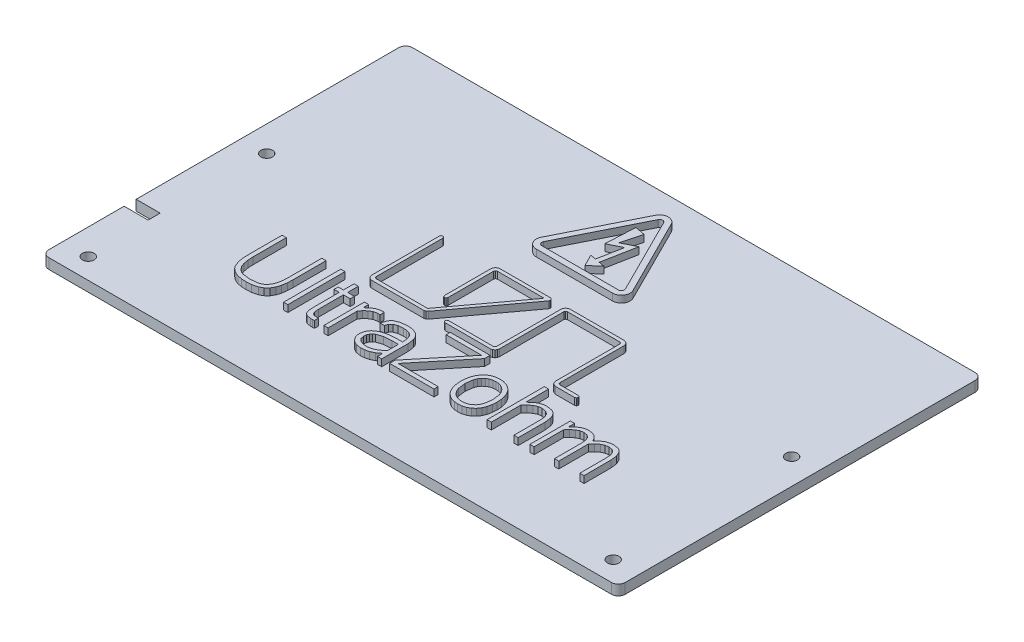
SolidWorks part; units mm, degrees
ref_plane "Ebene vorne" through (0, 0, 0) normal (0, 0, 1) x (1, 0, 0)
ref_plane "Ebene oben" through (0, 0, 0) normal (0, 1, 0) x (1, 0, 0)
ref_plane "Ebene rechts" through (0, 0, 0) normal (1, 0, 0) x (0, 0, -1)
sketch "Skizze1" plane through (0, 0, 0) normal (0, 1, 0) x (1, 0, 0)
  line L1 (-82, -53) -> (82, -53)
  line L2 (-84, -51) -> (-84, 51)
  line L3 (-82, 53) -> (82, 53)
  line L4 (84, -51) -> (84, 51)
  line L5 (-84, -53) -> (84, 53) construction
  line L6 (-84, 53) -> (84, -53) construction
  arc A0 (82, -53) -> (84, -51) centre (82, -51) ccw
  arc A1 (82, 53) -> (84, 51) centre (82, 51) cw
  arc A2 (-84, 51) -> (-82, 53) centre (-82, 51) cw
  arc A3 (-82, -53) -> (-84, -51) centre (-82, -51) cw
  point P0 (0, 0)
  dimension "D3" = 2
  dimension "D1" = 168
  dimension "D2" = 106
extrude "Aufsatz-Linear austragen1" add sketch "Skizze1" along normal blind 3
sketch "Skizze4" plane through (0, 3, 0) normal (0, 1, 0) x (1, 0, 0)
  line L0 (-84, 51) -> (-84, -51) construction
  line L1 (-84, -29.05) -> (-77, -29.05)
  line L2 (-84, -29.05) -> (-84, -25.55)
  line L3 (-84, -25.55) -> (-77, -25.55)
  line L4 (-77, -29.05) -> (-77, -25.55)
  line L5 (-77, -27.3) -> (-84, -27.3) construction
  line L6 (-82, -53) -> (82, -53) construction
  dimension "D1" = 25.7
  dimension "D2" = 3.5
  dimension "D3" = 7
extrude "Schnitt-Linear austragen3" cut sketch "Skizze4" against normal blind 3
sketch "Skizze9" plane through (0, 3, 0) normal (0, 1, 0) x (1, 0, 0)
  line L0 (-12.0391, -13.6755) -> (-27.171, -13.6755)
  line L1 (-27.171, -13.6755) -> (-27.7014, -13.5675)
  line L2 (-27.7014, -13.5675) -> (-28.1343, -13.2749)
  line L3 (-28.1343, -13.2749) -> (-28.4261, -12.8414)
  line L4 (-28.4261, -12.8414) -> (-28.5331, -12.3109)
  line L5 (-28.5331, -12.3109) -> (-28.5331, 7.3376)
  line L6 (-28.5331, 7.3376) -> (-28.3811, 7.7047)
  line L7 (-28.3811, 7.7047) -> (-28.014, 7.8567)
  line L8 (-28.014, 7.8567) -> (-27.6485, 7.7038)
  line L9 (-27.6485, 7.7038) -> (-27.4973, 7.3376)
  line L10 (-27.4973, 7.3376) -> (-27.4973, -12.1082)
  line L11 (-27.4973, -12.1082) -> (-27.3451, -12.4744)
  line L12 (-27.3451, -12.4744) -> (-26.9782, -12.6248)
  line L13 (-26.9782, -12.6248) -> (-12.0391, -12.6248)
  line L14 (-12.0391, -12.6248) -> (-11.9303, -12.568)
  line L15 (-11.9303, -12.568) -> (2.2992, 6.7146)
  line L16 (2.2992, 6.7146) -> (2.3115, 6.8581)
  line L17 (2.3115, 6.8581) -> (2.188, 6.9322)
  line L18 (2.188, 6.9322) -> (-11.2282, 6.9322)
  line L19 (-11.2282, 6.9322) -> (-11.5953, 6.7801)
  line L20 (-11.5953, 6.7801) -> (-11.7474, 6.413)
  line L21 (-11.7474, 6.413) -> (-11.7474, -6.9068)
  line L22 (-11.7474, -6.9068) -> (-11.8978, -7.2737)
  line L23 (-11.8978, -7.2737) -> (-12.2641, -7.4259)
  line L24 (-12.2641, -7.4259) -> (-12.6312, -7.2739)
  line L25 (-12.6312, -7.2739) -> (-12.7832, -6.9068)
  line L26 (-12.7832, -6.9068) -> (-12.7832, 6.596)
  line L27 (-12.7832, 6.596) -> (-12.6762, 7.1262)
  line L28 (-12.6762, 7.1262) -> (-12.3842, 7.5591)
  line L29 (-12.3842, 7.5591) -> (-11.9513, 7.8511)
  line L30 (-11.9513, 7.8511) -> (-11.4211, 7.9581)
  line L31 (-11.4211, 7.9581) -> (3.1645, 7.9581)
  line L32 (3.1645, 7.9581) -> (3.5356, 7.8718)
  line L33 (3.5356, 7.8718) -> (3.7978, 7.5953)
  line L34 (3.7978, 7.5953) -> (3.8644, 7.2202)
  line L35 (3.8644, 7.2202) -> (3.7133, 6.8704)
  line L36 (3.7133, 6.8704) -> (-11.1022, -13.181)
  line L37 (-11.1022, -13.181) -> (-11.515, -13.5337)
  line L38 (-11.515, -13.5337) -> (-12.0391, -13.6755)
  line L39 (-12.0391, -13.6755) -> (-12.0391, -13.6755)
  line L40 (31.9376, -13.6755) -> (26.3901, -13.6755)
  line L41 (26.3901, -13.6755) -> (25.8597, -13.5675)
  line L42 (25.8597, -13.5675) -> (25.4268, -13.2749)
  line L43 (25.4268, -13.2749) -> (25.135, -12.8414)
  line L44 (25.135, -12.8414) -> (25.028, -12.3109)
  line L45 (25.028, -12.3109) -> (25.028, 6.4056)
  line L46 (25.028, 6.4056) -> (24.8768, 6.7718)
  line L47 (24.8768, 6.7718) -> (24.5113, 6.9248)
  line L48 (24.5113, 6.9248) -> (9.2187, 6.9248)
  line L49 (9.2187, 6.9248) -> (8.8532, 6.7718)
  line L50 (8.8532, 6.7718) -> (8.702, 6.4056)
  line L51 (8.702, 6.4056) -> (8.702, -12.2985)
  line L52 (8.702, -12.2985) -> (8.6022, -12.8234)
  line L53 (8.6022, -12.8234) -> (8.3085, -13.2697)
  line L54 (8.3085, -13.2697) -> (7.8659, -13.569)
  line L55 (7.8659, -13.569) -> (7.3424, -13.6755)
  line L56 (7.3424, -13.6755) -> (-5.8514, -13.6755)
  line L57 (-5.8514, -13.6755) -> (-6.2185, -13.5234)
  line L58 (-6.2185, -13.5234) -> (-6.3705, -13.1563)
  line L59 (-6.3705, -13.1563) -> (-6.2185, -12.7892)
  line L60 (-6.2185, -12.7892) -> (-5.8514, -12.6372)
  line L61 (-5.8514, -12.6372) -> (7.1471, -12.6372)
  line L62 (7.1471, -12.6372) -> (7.514, -12.4867)
  line L63 (7.514, -12.4867) -> (7.6662, -12.1205)
  line L64 (7.6662, -12.1205) -> (7.6662, 6.596)
  line L65 (7.6662, 6.596) -> (7.7699, 7.1172)
  line L66 (7.7699, 7.1172) -> (8.0652, 7.5591)
  line L67 (8.0652, 7.5591) -> (8.5071, 7.8544)
  line L68 (8.5071, 7.8544) -> (9.0284, 7.9581)
  line L69 (9.0284, 7.9581) -> (24.7016, 7.9581)
  line L70 (24.7016, 7.9581) -> (25.2229, 7.8544)
  line L71 (25.2229, 7.8544) -> (25.6648, 7.5591)
  line L72 (25.6648, 7.5591) -> (25.9601, 7.1172)
  line L73 (25.9601, 7.1172) -> (26.0638, 6.596)
  line L74 (26.0638, 6.596) -> (26.0638, -12.1106)
  line L75 (26.0638, -12.1106) -> (26.216, -12.4768)
  line L76 (26.216, -12.4768) -> (26.5829, -12.6273)
  line L77 (26.5829, -12.6273) -> (31.9376, -12.6273)
  line L78 (31.9376, -12.6273) -> (32.3031, -12.7802)
  line L79 (32.3031, -12.7802) -> (32.4542, -13.1464)
  line L80 (32.4542, -13.1464) -> (32.3066, -13.5191)
  line L81 (32.3066, -13.5191) -> (31.9376, -13.6755)
  line L82 (-45.2447, -32.34) -> (-46.5411, -32.2746)
  line L83 (-46.5411, -32.2746) -> (-47.8157, -32.0285)
  line L84 (-47.8157, -32.0285) -> (-48.7416, -31.6863)
  line L85 (-48.7416, -31.6863) -> (-49.5907, -31.1831)
  line L86 (-49.5907, -31.1831) -> (-50.2138, -30.6155)
  line L87 (-50.2138, -30.6155) -> (-50.7106, -29.9347)
  line L88 (-50.7106, -29.9347) -> (-51.341, -28.4118)
  line L89 (-51.341, -28.4118) -> (-51.6104, -26.7357)
  line L90 (-51.6104, -26.7357) -> (-51.6648, -25.0448)
  line L91 (-51.6648, -25.0448) -> (-51.6648, -15.3565)
  line L92 (-51.6648, -15.3565) -> (-50.4287, -15.3565)
  line L93 (-50.4287, -15.3565) -> (-50.4287, -24.9978)
  line L94 (-50.4287, -24.9978) -> (-50.3617, -26.5597)
  line L95 (-50.3617, -26.5597) -> (-50.0826, -28.0979)
  line L96 (-50.0826, -28.0979) -> (-49.694, -29.0952)
  line L97 (-49.694, -29.0952) -> (-49.0691, -29.9643)
  line L98 (-49.0691, -29.9643) -> (-48.3174, -30.5337)
  line L99 (-48.3174, -30.5337) -> (-47.4399, -30.879)
  line L100 (-47.4399, -30.879) -> (-45.2373, -31.1262)
  line L101 (-45.2373, -31.1262) -> (-43.0124, -30.879)
  line L102 (-43.0124, -30.879) -> (-42.1317, -30.5347)
  line L103 (-42.1317, -30.5347) -> (-41.3832, -29.9569)
  line L104 (-41.3832, -29.9569) -> (-40.7738, -29.0846)
  line L105 (-40.7738, -29.0846) -> (-40.3944, -28.0904)
  line L106 (-40.3944, -28.0904) -> (-40.1223, -26.5554)
  line L107 (-40.1223, -26.5554) -> (-40.0582, -24.9978)
  line L108 (-40.0582, -24.9978) -> (-40.0582, -15.3565)
  line L109 (-40.0582, -15.3565) -> (-38.8221, -15.3565)
  line L110 (-38.8221, -15.3565) -> (-38.8221, -25.0473)
  line L111 (-38.8221, -25.0473) -> (-38.8865, -26.5926)
  line L112 (-38.8865, -26.5926) -> (-39.1138, -28.1226)
  line L113 (-39.1138, -28.1226) -> (-39.4909, -29.3269)
  line L114 (-39.4909, -29.3269) -> (-40.1274, -30.4167)
  line L115 (-40.1274, -30.4167) -> (-41.0155, -31.2668)
  line L116 (-41.0155, -31.2668) -> (-42.1002, -31.8456)
  line L117 (-42.1002, -31.8456) -> (-43.6494, -32.2393)
  line L118 (-43.6494, -32.2393) -> (-45.2447, -32.34)
  line L119 (-33.2944, -32.036) -> (-34.5305, -32.036)
  line L120 (-34.5305, -32.036) -> (-34.5305, -15.3565)
  line L121 (-34.5305, -15.3565) -> (-33.2944, -15.3565)
  line L122 (-33.2944, -15.3565) -> (-33.2944, -32.036)
  line L123 (-25.4306, -32.1423) -> (-25.9522, -32.1892)
  line L124 (-25.9522, -32.1892) -> (-26.4738, -32.2041)
  line L125 (-26.4738, -32.2041) -> (-27.7569, -31.9816)
  line L126 (-27.7569, -31.9816) -> (-28.1822, -31.7113)
  line L127 (-28.1822, -31.7113) -> (-28.4985, -31.319)
  line L128 (-28.4985, -31.319) -> (-28.8298, -30.2165)
  line L129 (-28.8298, -30.2165) -> (-28.9064, -28.6689)
  line L130 (-28.9064, -28.6689) -> (-28.9064, -21.4503)
  line L131 (-28.9064, -21.4503) -> (-30.4268, -21.4503)
  line L132 (-30.4268, -21.4503) -> (-30.4268, -20.2316)
  line L133 (-30.4268, -20.2316) -> (-28.9064, -20.2316)
  line L134 (-28.9064, -20.2316) -> (-28.9064, -17.1365)
  line L135 (-28.9064, -17.1365) -> (-27.6704, -17.1365)
  line L136 (-27.6704, -17.1365) -> (-27.6704, -20.2291)
  line L137 (-27.6704, -20.2291) -> (-25.7198, -20.2291)
  line L138 (-25.7198, -20.2291) -> (-25.7198, -21.4478)
  line L139 (-25.7198, -21.4478) -> (-27.6704, -21.4478)
  line L140 (-27.6704, -21.4478) -> (-27.6704, -28.7728)
  line L141 (-27.6704, -28.7728) -> (-27.5616, -29.9396)
  line L142 (-27.5616, -29.9396) -> (-27.2402, -30.6095)
  line L143 (-27.2402, -30.6095) -> (-26.7112, -30.9136)
  line L144 (-26.7112, -30.9136) -> (-25.9967, -30.9828)
  line L145 (-25.9967, -30.9828) -> (-25.705, -30.9828)
  line L146 (-25.705, -30.9828) -> (-25.4281, -30.968)
  line L147 (-25.4281, -30.968) -> (-25.4306, -32.1423)
  line L148 (-17.3047, -21.1759) -> (-17.6731, -21.1462)
  line L149 (-17.6731, -21.1462) -> (-18.1205, -21.1462)
  line L150 (-18.1205, -21.1462) -> (-19.1366, -21.3588)
  line L151 (-19.1366, -21.3588) -> (-20.0735, -21.9151)
  line L152 (-20.0735, -21.9151) -> (-20.9017, -22.6913)
  line L153 (-20.9017, -22.6913) -> (-21.5617, -23.5813)
  line L154 (-21.5617, -23.5813) -> (-21.5617, -32.036)
  line L155 (-21.5617, -32.036) -> (-22.7978, -32.036)
  line L156 (-22.7978, -32.036) -> (-22.7978, -20.2316)
  line L157 (-22.7978, -20.2316) -> (-21.5617, -20.2316)
  line L158 (-21.5617, -20.2316) -> (-21.5617, -21.8607)
  line L159 (-21.5617, -21.8607) -> (-20.5259, -20.8718)
  line L160 (-20.5259, -20.8718) -> (-19.5371, -20.2761)
  line L161 (-19.5371, -20.2761) -> (-18.6075, -19.9942)
  line L162 (-18.6075, -19.9942) -> (-17.7942, -19.9275)
  line L163 (-17.7942, -19.9275) -> (-17.5643, -19.9275)
  line L164 (-17.5643, -19.9275) -> (-17.3171, -19.9497)
  line L165 (-17.3171, -19.9497) -> (-17.3047, -21.1759)
  line L166 (-7.169, -30.5131) -> (-8.4051, -31.4179)
  line L167 (-8.4051, -31.4179) -> (-9.5793, -31.9816)
  line L168 (-9.5793, -31.9816) -> (-10.7239, -32.2634)
  line L169 (-10.7239, -32.2634) -> (-11.8759, -32.34)
  line L170 (-11.8759, -32.34) -> (-13.3345, -32.1052)
  line L171 (-13.3345, -32.1052) -> (-14.5013, -31.4352)
  line L172 (-14.5013, -31.4352) -> (-15.2776, -30.3821)
  line L173 (-15.2776, -30.3821) -> (-15.4947, -29.7167)
  line L174 (-15.4947, -29.7167) -> (-15.5619, -29.02)
  line L175 (-15.5619, -29.02) -> (-15.4598, -28.0761)
  line L176 (-15.4598, -28.0761) -> (-15.1192, -27.2069)
  line L177 (-15.1192, -27.2069) -> (-14.5642, -26.4563)
  line L178 (-14.5642, -26.4563) -> (-13.819, -25.868)
  line L179 (-13.819, -25.868) -> (-12.8385, -25.3748)
  line L180 (-12.8385, -25.3748) -> (-11.6398, -25.0225)
  line L181 (-11.6398, -25.0225) -> (-10.223, -24.8112)
  line L182 (-10.223, -24.8112) -> (-8.588, -24.7407)
  line L183 (-8.588, -24.7407) -> (-7.1764, -24.7407)
  line L184 (-7.1764, -24.7407) -> (-7.2679, -23.3094)
  line L185 (-7.2679, -23.3094) -> (-7.698, -22.1746)
  line L186 (-7.698, -22.1746) -> (-8.138, -21.7262)
  line L187 (-8.138, -21.7262) -> (-8.6869, -21.4207)
  line L188 (-8.6869, -21.4207) -> (-9.5724, -21.1974)
  line L189 (-9.5724, -21.1974) -> (-10.4841, -21.1462)
  line L190 (-10.4841, -21.1462) -> (-11.947, -21.2754)
  line L191 (-11.947, -21.2754) -> (-12.9933, -21.6629)
  line L192 (-12.9933, -21.6629) -> (-13.6706, -22.3326)
  line L193 (-13.6706, -22.3326) -> (-13.9822, -23.2327)
  line L194 (-13.9822, -23.2327) -> (-15.196, -23.2327)
  line L195 (-15.196, -23.2327) -> (-14.7733, -21.7717)
  line L196 (-14.7733, -21.7717) -> (-14.3839, -21.2025)
  line L197 (-14.3839, -21.2025) -> (-13.8759, -20.7408)
  line L198 (-13.8759, -20.7408) -> (-12.4637, -20.1296)
  line L199 (-12.4637, -20.1296) -> (-10.4965, -19.9275)
  line L200 (-10.4965, -19.9275) -> (-9.4282, -19.9913)
  line L201 (-9.4282, -19.9913) -> (-8.3853, -20.2316)
  line L202 (-8.3853, -20.2316) -> (-7.626, -20.5846)
  line L203 (-7.626, -20.5846) -> (-6.9712, -21.1067)
  line L204 (-6.9712, -21.1067) -> (-6.4927, -21.7528)
  line L205 (-6.4927, -21.7528) -> (-6.1802, -22.4936)
  line L206 (-6.1802, -22.4936) -> (-5.9329, -24.3279)
  line L207 (-5.9329, -24.3279) -> (-5.9329, -32.036)
  line L208 (-5.9329, -32.036) -> (-7.169, -32.036)
  line L209 (-7.169, -32.036) -> (-7.169, -30.5131)
  line L210 (-7.169, -25.9595) -> (-9.0256, -25.9595)
  line L211 (-9.0256, -25.9595) -> (-11.3599, -26.1498)
  line L212 (-11.3599, -26.1498) -> (-13.0131, -26.7209)
  line L213 (-13.0131, -26.7209) -> (-13.566, -27.1069)
  line L214 (-13.566, -27.1069) -> (-13.9827, -27.6211)
  line L215 (-13.9827, -27.6211) -> (-14.2427, -28.2296)
  line L216 (-14.2427, -28.2296) -> (-14.3258, -28.8988)
  line L217 (-14.3258, -28.8988) -> (-14.1223, -29.8246)
  line L218 (-14.1223, -29.8246) -> (-13.4952, -30.5354)
  line L219 (-13.4952, -30.5354) -> (-12.5131, -30.9748)
  line L220 (-12.5131, -30.9748) -> (-11.2233, -31.1213)
  line L221 (-11.2233, -31.1213) -> (-10.0021, -30.9309)
  line L222 (-10.0021, -30.9309) -> (-8.8871, -30.4365)
  line L223 (-8.8871, -30.4365) -> (-7.9279, -29.7591)
  line L224 (-7.9279, -29.7591) -> (-7.169, -29.0348)
  line L225 (-7.169, -29.0348) -> (-7.169, -25.9595)
  line L226 (9.2954, -32.036) -> (-3.6388, -32.036)
  line L227 (-3.6388, -32.036) -> (-3.6388, -30.4217)
  line L228 (-3.6388, -30.4217) -> (7.7132, -16.5778)
  line L229 (7.7132, -16.5778) -> (-2.6401, -16.5778)
  line L230 (-2.6401, -16.5778) -> (-2.6401, -15.3565)
  line L231 (-2.6401, -15.3565) -> (8.9789, -15.3565)
  line L232 (8.9789, -15.3565) -> (8.9789, -16.9881)
  line L233 (8.9789, -16.9881) -> (-2.3929, -30.8172)
  line L234 (-2.3929, -30.8172) -> (9.2954, -30.8172)
  line L235 (9.2954, -30.8172) -> (9.2954, -32.036)
  line L236 (16.4892, -19.9275) -> (17.6108, -20.027)
  line L237 (17.6108, -20.027) -> (18.6894, -20.3502)
  line L238 (18.6894, -20.3502) -> (19.5967, -20.8628)
  line L239 (19.5967, -20.8628) -> (20.3631, -21.569)
  line L240 (20.3631, -21.569) -> (20.9971, -22.4874)
  line L241 (20.9971, -22.4874) -> (21.4335, -23.5145)
  line L242 (21.4335, -23.5145) -> (21.7144, -24.8122)
  line L243 (21.7144, -24.8122) -> (21.808, -26.1301)
  line L244 (21.808, -26.1301) -> (21.7144, -27.4479)
  line L245 (21.7144, -27.4479) -> (21.4335, -28.7456)
  line L246 (21.4335, -28.7456) -> (20.999, -29.778)
  line L247 (20.999, -29.778) -> (20.368, -30.7035)
  line L248 (20.368, -30.7035) -> (19.5999, -31.4091)
  line L249 (19.5999, -31.4091) -> (18.6919, -31.9222)
  line L250 (18.6919, -31.9222) -> (17.6183, -32.2325)
  line L251 (17.6183, -32.2325) -> (16.5152, -32.336)
  line L252 (16.5152, -32.336) -> (15.4121, -32.2325)
  line L253 (15.4121, -32.2325) -> (14.3385, -31.9222)
  line L254 (14.3385, -31.9222) -> (13.4343, -31.4143)
  line L255 (13.4343, -31.4143) -> (12.6723, -30.7109)
  line L256 (12.6723, -30.7109) -> (12.0371, -29.7855)
  line L257 (12.0371, -29.7855) -> (11.5969, -28.753)
  line L258 (11.5969, -28.753) -> (11.3123, -27.4481)
  line L259 (11.3123, -27.4481) -> (11.2174, -26.1226)
  line L260 (11.2174, -26.1226) -> (11.3123, -24.7972)
  line L261 (11.3123, -24.7972) -> (11.5969, -23.4923)
  line L262 (11.5969, -23.4923) -> (12.032, -22.4664)
  line L263 (12.032, -22.4664) -> (12.6649, -21.5492)
  line L264 (12.6649, -21.5492) -> (13.432, -20.8473)
  line L265 (13.432, -20.8473) -> (14.3385, -20.3379)
  line L266 (14.3385, -20.3379) -> (15.3933, -20.0246)
  line L267 (15.3933, -20.0246) -> (16.4892, -19.9275)
  line L268 (16.4892, -31.1213) -> (17.3305, -31.0481)
  line L269 (17.3305, -31.0481) -> (18.1406, -30.8098)
  line L270 (18.1406, -30.8098) -> (18.8389, -30.4147)
  line L271 (18.8389, -30.4147) -> (19.4237, -29.8654)
  line L272 (19.4237, -29.8654) -> (19.9207, -29.1227)
  line L273 (19.9207, -29.1227) -> (20.2592, -28.2956)
  line L274 (20.2592, -28.2956) -> (20.5608, -26.1177)
  line L275 (20.5608, -26.1177) -> (20.2592, -23.9397)
  line L276 (20.2592, -23.9397) -> (19.9216, -23.1204)
  line L277 (19.9216, -23.1204) -> (19.4237, -22.3873)
  line L278 (19.4237, -22.3873) -> (18.8366, -21.8474)
  line L279 (18.8366, -21.8474) -> (18.1406, -21.4577)
  line L280 (18.1406, -21.4577) -> (17.3222, -21.2242)
  line L281 (17.3222, -21.2242) -> (16.4818, -21.1463)
  line L282 (16.4818, -21.1463) -> (15.6415, -21.2242)
  line L283 (15.6415, -21.2242) -> (14.823, -21.4577)
  line L284 (14.823, -21.4577) -> (14.1271, -21.8474)
  line L285 (14.1271, -21.8474) -> (13.54, -22.3873)
  line L286 (13.54, -22.3873) -> (13.0443, -23.12)
  line L287 (13.0443, -23.12) -> (12.7118, -23.9397)
  line L288 (12.7118, -23.9397) -> (12.4201, -26.1177)
  line L289 (12.4201, -26.1177) -> (12.7118, -28.2956)
  line L290 (12.7118, -28.2956) -> (13.0454, -29.123)
  line L291 (13.0454, -29.123) -> (13.54, -29.8654)
  line L292 (13.54, -29.8654) -> (14.1248, -30.4147)
  line L293 (14.1248, -30.4147) -> (14.823, -30.8098)
  line L294 (14.823, -30.8098) -> (15.6406, -31.0488)
  line L295 (15.6406, -31.0488) -> (16.4892, -31.1213)
  line L296 (26.0143, -21.9843) -> (27.1565, -20.9163)
  line L297 (27.1565, -20.9163) -> (28.2491, -20.2934)
  line L298 (28.2491, -20.2934) -> (29.2627, -20.0041)
  line L299 (29.2627, -20.0041) -> (30.1749, -19.9275)
  line L300 (30.1749, -19.9275) -> (31.781, -20.1959)
  line L301 (31.781, -20.1959) -> (32.412, -20.5313)
  line L302 (32.412, -20.5313) -> (32.9283, -21.001)
  line L303 (32.9283, -21.001) -> (33.3298, -21.6049)
  line L304 (33.3298, -21.6049) -> (33.6166, -22.3429)
  line L305 (33.6166, -22.3429) -> (33.846, -24.2216)
  line L306 (33.846, -24.2216) -> (33.846, -32.036)
  line L307 (33.846, -32.036) -> (32.61, -32.036)
  line L308 (32.61, -32.036) -> (32.61, -24.3279)
  line L309 (32.61, -24.3279) -> (32.4641, -22.9039)
  line L310 (32.4641, -22.9039) -> (31.9895, -21.9151)
  line L311 (31.9895, -21.9151) -> (31.1292, -21.3366)
  line L312 (31.1292, -21.3366) -> (29.8313, -21.1462)
  line L313 (29.8313, -21.1462) -> (28.8164, -21.3009)
  line L314 (28.8164, -21.3009) -> (27.8882, -21.7396)
  line L315 (27.8882, -21.7396) -> (26.8886, -22.5114)
  line L316 (26.8886, -22.5114) -> (26.0069, -23.4157)
  line L317 (26.0069, -23.4157) -> (26.0069, -32.036)
  line L318 (26.0069, -32.036) -> (24.7709, -32.036)
  line L319 (24.7709, -32.036) -> (24.7709, -15.3565)
  line L320 (24.7709, -15.3565) -> (26.0069, -15.3565)
  line L321 (26.0069, -15.3565) -> (26.0143, -21.9843)
  line L322 (53.0273, -32.036) -> (51.7912, -32.036)
  line L323 (51.7912, -32.036) -> (51.7912, -24.3279)
  line L324 (51.7912, -24.3279) -> (51.6589, -22.8736)
  line L325 (51.6589, -22.8736) -> (51.2622, -21.8928)
  line L326 (51.2622, -21.8928) -> (50.5255, -21.3366)
  line L327 (50.5255, -21.3366) -> (49.3957, -21.1512)
  line L328 (49.3957, -21.1512) -> (48.3949, -21.311)
  line L329 (48.3949, -21.311) -> (47.4823, -21.7519)
  line L330 (47.4823, -21.7519) -> (46.5116, -22.5285)
  line L331 (46.5116, -22.5285) -> (45.6776, -23.4503)
  line L332 (45.6776, -23.4503) -> (45.6776, -32.0409)
  line L333 (45.6776, -32.0409) -> (44.4416, -32.0409)
  line L334 (44.4416, -32.0409) -> (44.4416, -24.3279)
  line L335 (44.4416, -24.3279) -> (44.3279, -22.8817)
  line L336 (44.3279, -22.8817) -> (43.9348, -21.8928)
  line L337 (43.9348, -21.8928) -> (43.1931, -21.3292)
  line L338 (43.1931, -21.3292) -> (42.0807, -21.1462)
  line L339 (42.0807, -21.1462) -> (41.1122, -21.3042)
  line L340 (41.1122, -21.3042) -> (40.2365, -21.747)
  line L341 (40.2365, -21.747) -> (39.2933, -22.5332)
  line L342 (39.2933, -22.5332) -> (38.4714, -23.4453)
  line L343 (38.4714, -23.4453) -> (38.4714, -32.036)
  line L344 (38.4714, -32.036) -> (37.2353, -32.036)
  line L345 (37.2353, -32.036) -> (37.2353, -20.2316)
  line L346 (37.2353, -20.2316) -> (38.4714, -20.2316)
  line L347 (38.4714, -20.2316) -> (38.4714, -21.9843)
  line L348 (38.4714, -21.9843) -> (39.6308, -20.8941)
  line L349 (39.6308, -20.8941) -> (40.6592, -20.2761)
  line L350 (40.6592, -20.2761) -> (41.5813, -19.9942)
  line L351 (41.5813, -19.9942) -> (42.4169, -19.9275)
  line L352 (42.4169, -19.9275) -> (43.4453, -20.0461)
  line L353 (43.4453, -20.0461) -> (44.3946, -20.459)
  line L354 (44.3946, -20.459) -> (45.1274, -21.1727)
  line L355 (45.1274, -21.1727) -> (45.5788, -22.0906)
  line L356 (45.5788, -22.0906) -> (46.5528, -21.0301)
  line L357 (46.5528, -21.0301) -> (47.5985, -20.3675)
  line L358 (47.5985, -20.3675) -> (48.6664, -20.0264)
  line L359 (48.6664, -20.0264) -> (49.7097, -19.9275)
  line L360 (49.7097, -19.9275) -> (51.1556, -20.1959)
  line L361 (51.1556, -20.1959) -> (51.7235, -20.5313)
  line L362 (51.7235, -20.5313) -> (52.188, -21.001)
  line L363 (52.188, -21.001) -> (52.8069, -22.3429)
  line L364 (52.8069, -22.3429) -> (53.0124, -24.2216)
  line L365 (53.0124, -24.2216) -> (53.0273, -32.036)
extrude "Aufsatz-Linear austragen2" add sketch "Skizze9" along normal blind 2 contours L118 L117 L116 L115 L114 L113 L112 L111 L110 L109 L108 L107 L106 L105 L104 L103 L102 L101 L100 L99 L98 L97 L96 L95 L94 L93 L92 L91 L90 L89 L88 L87 L86 L85 L84 L83 L82 | L122 L121 L120 L119 | L147 L146 L145 L144 L143 L142 L141 L140 L139 L138 L137 L136 L135 L134 L133 L132 L131 L130 L129 L128 L127 L126 L125 L124 L123 | L165 L164 L163 L162 L161 L160 L159 L158 L157 L156 L155 L154 L153 L152 L151 L150 L149 L148 | L209 L208 L207 L206 L205 L204 L203 L202 L201 L200 L199 L198 L197 L196 L195 L194 L193 L192 L191 L190 L189 L188 L187 L186 L185 L184 L183 L182 L181 L180 L179 L178 L177 L176 L175 L174 L173 L172 L171 L170 L169 L168 L167 L166 L225 L224 L223 L222 L221 L220 | L235 L234 L233 L232 L231 L230 L229 L228 L227 L226 | L267 L266 L265 L264 L263 L262 L261 L260 L259 L258 L257 L256 L255 L254 L253 L252 L251 L250 L249 L248 L247 L246 L245 L244 L243 L242 L241 L240 L239 L238 L237 L236 L295 L294 L293 L292 L291 L290 L289 L288 L287 L286 L285 L284 L283 L282 L281 L280 L279 L278 | L321 L320 L319 L318 L317 L316 L315 L314 L313 L312 L311 L310 L309 L308 L307 L306 L305 L304 L303 L302 L301 L300 L299 L298 L297 L296 | L365 L364 L363 L362 L361 L360 L359 L358 L357 L356 L355 L354 L353 L352 L351 L350 L349 L348 L347 L346 L345 L344 L343 L342 L341 L340 L339 L338 L337 L336 L335 L334 L333 L332 L331 L330 L329 L328 L327 L326 L325 L324 L323 L322 | L81 L80 L79 L78 L77 L76 L75 L74 L73 L72 L71 L70 L69 L68 L67 L66 L65 L64 L63 L62 L61 L60 L59 L58 L57 L56 L55 L54 L53 L52 L51 L50 L49 L48 L47 L46 L45 L44 L43 L42 L41 L40 | L38 L37 L36 L35 L34 L33 L32 L31 L30 L29 L28 L27 L26 L25 L24 L23 L22 L21 L20 L19 L18 L17 L16 L15 L14 L13 L12 L11 L10 L9 L8 L7 L6 L5 L4 L3 L2 L1 L0
sketch "Skizze10" plane through (0, 3, 0) normal (0, 1, 0) x (1, 0, 0)
  line L0 (-82, -53) -> (82, -53) construction
  line L1 (-84, -29.05) -> (-84, -51) construction
  circle A0 centre (-76.5, -47) radius 1.7
  circle A1 centre (76.5, -47) radius 1.7
  circle A2 centre (76.5, 5) radius 1.7
  circle A3 centre (-76.5, 5) radius 1.7
  dimension "D1" = 3.4
  dimension "D3" = 7.5
  dimension "D2" = 6
  dimension "D4" = 2
  dimension "D5" = 2
extrude "Schnitt-Linear austragen4" cut sketch "Skizze10" against normal through all
sketch "Skizze14" plane through (0, 3, 0) normal (0, 1, 0) x (1, 0, 0)
  line L0 (-11.1302, 18.1999) -> (11.1302, 18.1999)
  line L1 (-11.1302, 18.1999) -> (11.1302, 18.1999)
  line L5 (-0.7951, 43.3979) -> (-11.9253, 21.1375)
  line L6 (11.9253, 21.1375) -> (0.7951, 43.3979)
  line L7 (-11.1302, 19.8509) -> (11.1302, 19.8509)
  line L10 (0.1171, 21.1537) -> (-1.639, 24.6111)
  line L11 (-1.639, 24.6111) -> (0.0098, 24.2943)
  line L12 (0.0098, 24.2943) -> (1.3847, 31.4495)
  line L13 (1.3847, 31.4495) -> (-2.482, 29.5379)
  line L14 (-2.482, 29.5379) -> (-2.0542, 38.1676)
  line L15 (-2.0542, 38.1676) -> (0.885, 37.6028)
  line L16 (0.885, 37.6028) -> (-0.6432, 31.8211)
  line L17 (-0.6432, 31.8211) -> (3.2472, 33.7444)
  line L18 (3.2472, 33.7444) -> (1.3808, 24.0308)
  line L19 (1.3808, 24.0308) -> (3.0296, 23.714)
  line L20 (3.0296, 23.714) -> (0.1171, 21.1537)
  line L21 (-11.1302, 19.8509) -> (11.1302, 19.8509)
  line L22 (11.9253, 21.1375) -> (0.7951, 43.3979)
  line L25 (13.402, 21.8759) -> (2.2718, 44.1363)
  line L27 (-2.2718, 44.1363) -> (-13.402, 21.8759)
  line L28 (13.402, 21.8759) -> (2.2718, 44.1363)
  line L29 (0.1171, 21.1537) -> (-1.639, 24.6111)
  line L30 (-1.639, 24.6111) -> (0.0098, 24.2943)
  line L31 (0.0098, 24.2943) -> (1.3847, 31.4495)
  line L32 (1.3847, 31.4495) -> (-2.482, 29.5379)
  line L33 (-2.482, 29.5379) -> (-2.0542, 38.1676)
  line L34 (-2.0542, 38.1676) -> (0.885, 37.6028)
  line L35 (0.885, 37.6028) -> (-0.6432, 31.8211)
  line L36 (-0.6432, 31.8211) -> (3.2472, 33.7444)
  line L37 (3.2472, 33.7444) -> (1.3808, 24.0308)
  line L38 (1.3808, 24.0308) -> (3.0296, 23.714)
  line L39 (3.0296, 23.714) -> (0.1171, 21.1537)
  spline S1 degree 2 poles (-13.6702, 20.7399) (-13.6702, 18.1999) (-11.1302, 18.1999) knots 0 0 0 1 1 1 weights 1 0.707107 1
  spline S5 degree 2 poles (-12.0192, 20.7399) (-12.0192, 20.9498) (-11.9253, 21.1375) knots 0 0 0 1 1 1 weights 1 0.910926 0.87603
  spline S6 degree 2 poles (-12.0192, 20.7399) (-12.0192, 19.8509) (-11.1302, 19.8509) knots 0 0 0 1 1 1 weights 1 0.707107 1
  spline S8 degree 2 poles (11.1302, 19.8509) (12.0192, 19.8509) (12.0192, 20.7399) (12.0192, 20.9498) (11.9253, 21.1375) knots 0 0 0 0.766804 0.766804 1 1 1 weights 1 0.707107 1 0.910927 0.876031
  spline S12 degree 2 poles (-12.0192, 20.7399) (-12.0192, 20.3717) (-11.7588, 20.1113) (-11.4984, 19.8509) (-11.1302, 19.8509) knots 0 0 0 0.5 0.5 1 1 1 weights 1 0.92388 1 0.92388 1
  spline S13 degree 2 poles (11.1302, 19.8509) (11.6258, 19.8509) (11.8864, 20.2726) (12.147, 20.6942) (11.9253, 21.1375) knots 0 0 0 0.5 0.5 1 1 1 weights 1 0.873422 1 0.873422 1
  spline S14 degree 2 poles (0.7951, 43.3979) (0.5494, 43.8893) (0, 43.8893) (-0.5494, 43.8893) (-0.7951, 43.3979) knots 0 0 0 0.5 0.5 1 1 1 weights 1 0.850651 1 0.850651 1
  spline S18 degree 2 poles (11.1302, 18.1999) (12.5463, 18.1999) (13.2908, 19.4046) (14.0354, 20.6092) (13.402, 21.8759) knots 0 0 0 0.5 0.5 1 1 1 weights 1 0.873422 1 0.873422 1
  spline S20 degree 2 poles (-13.402, 21.8759) (-13.6702, 21.3396) (-13.6702, 20.7399) knots 0 0 0 1 1 1 weights 1 0.973249 1
  spline S21 degree 2 poles (-13.402, 21.8759) (-13.6702, 21.3396) (-13.6702, 20.7399) knots 0 0 0 1 1 1 weights 0.876031 0.910927 1
  spline S22 degree 2 poles (11.1302, 18.1999) (13.6702, 18.1999) (13.6702, 20.7399) (13.6702, 21.3396) (13.402, 21.8759) knots 0 0 0 0.766804 0.766804 1 1 1 weights 1 0.707107 1 0.910927 0.876031
  spline S23 degree 2 poles (2.2718, 44.1363) (1.5698, 45.5403) (0, 45.5403) (-1.5698, 45.5403) (-2.2718, 44.1363) knots 0 0 0 0.5 0.5 1 1 1 weights 0.876031 0.79618 1 0.79618 0.876031
extrude "Aufsatz-Linear austragen3" add sketch "Skizze14" along normal blind 2 contours L25 S23 L27 S20 S1 L0 S18 S14 L6 S8 L7 S6 S5 L5 | L20 L19 L18 L17 L16 L15 L14 L13 L12 L11 L10
